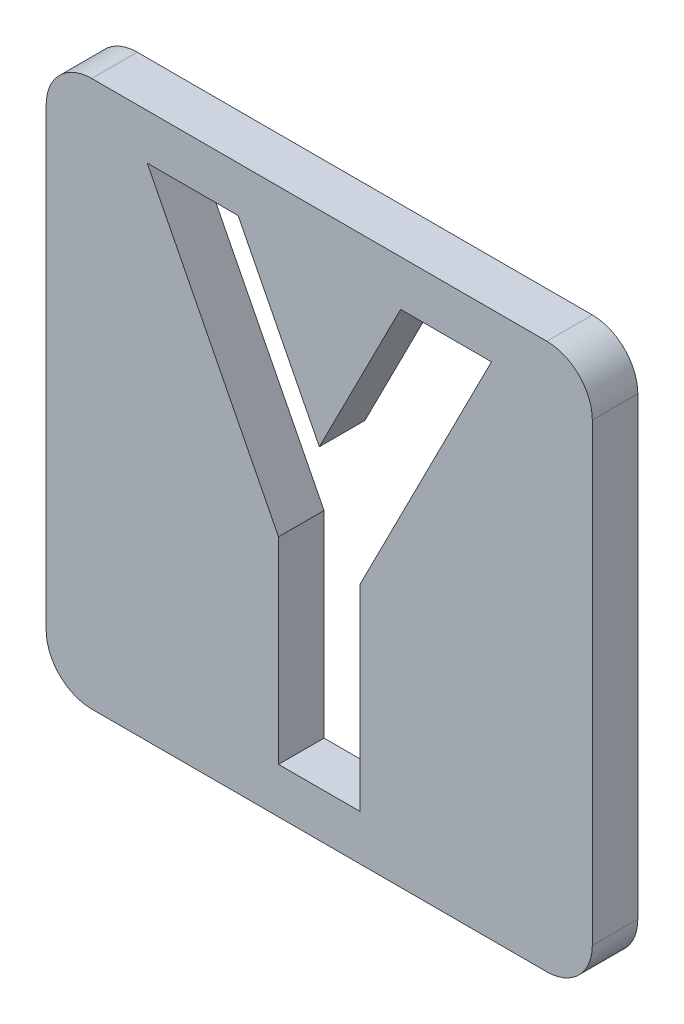
SolidWorks part; units mm, degrees
ref_plane "Front Plane" through (0, 0, 0) normal (0, 0, 1) x (1, 0, 0)
ref_plane "Top Plane" through (0, 0, 0) normal (0, 1, 0) x (1, 0, 0)
ref_plane "Right Plane" through (0, 0, 0) normal (1, 0, 0) x (0, 0, -1)
sketch "Sketch1" plane through (0, 0, 0) normal (0, 0, 1) x (1, 0, 0)
  line L1 (-50, 60) -> (50, 60)
  line L2 (-60, 50) -> (-60, -50)
  line L3 (-50, -60) -> (50, -60)
  line L4 (60, 50) -> (60, -50)
  line L5 (-60, 60) -> (60, -60) construction
  line L6 (-60, -60) -> (60, 60) construction
  arc A0 (-60, -50) -> (-50, -60) centre (-50, -50) ccw
  arc A1 (50, -60) -> (60, -50) centre (50, -50) ccw
  arc A2 (50, 60) -> (60, 50) centre (50, 50) cw
  arc A3 (-50, 60) -> (-60, 50) centre (-50, 50) ccw
  point P0 (0, 0)
  dimension "D3" = 10
  dimension "D1" = 120
  dimension "D2" = 120
extrude "Boss-Extrude1" add sketch "Sketch1" along normal blind 10 contours A3 L2 A0 L3 A1 L4 A2 L1
sketch "Sketch2" plane through (0, 0, 10) normal (0, 0, 1) x (1, 0, 0)
  line L0 (0, 0) -> (0, 40) construction
  line L1 (-50, 50) -> (50, 50) construction
  line L2 (-50, 50) -> (-50, -50) construction
  line L3 (-50, -50) -> (50, -50) construction
  line L4 (50, 50) -> (50, -50) construction
  line L5 (-50, 50) -> (50, -50) construction
  line L6 (-50, -50) -> (50, 50) construction
  line L7 (0, 40) -> (-40, 40) construction
  line L8 (-40, 40) -> (-40, 0) construction
  line L9 (-40, 0) -> (0, 0) construction
  line L11 (0, 20) -> (-20, 20) construction
  line L12 (-20, 40) -> (-20, 20) construction
  circle A0 centre (0, 40) radius 4 construction
  circle A1 centre (0, 20) radius 4 construction
  circle A2 centre (0, 0) radius 4 construction
  circle A3 centre (-20, 20) radius 4 construction
  circle A4 centre (-20, 40) radius 4 construction
  circle A5 centre (-40, 40) radius 4 construction
  circle A6 centre (0, 0) radius 4 construction
  circle A7 centre (20, 0) radius 4 construction
  circle A8 centre (40, 0) radius 4 construction
  circle A9 centre (40, 20) radius 4 construction
  circle A10 centre (40, 40) radius 4 construction
  circle A11 centre (20, 20) radius 4 construction
  circle A12 centre (0, 0) radius 4 construction
  circle A13 centre (0, -20) radius 4 construction
  circle A14 centre (0, -40) radius 4 construction
  circle A15 centre (20, -40) radius 4 construction
  circle A16 centre (40, -40) radius 4 construction
  circle A17 centre (20, -20) radius 4 construction
  circle A18 centre (0, 0) radius 4 construction
  circle A19 centre (-20, 0) radius 4 construction
  circle A20 centre (-40, 0) radius 4 construction
  circle A21 centre (-40, -20) radius 4 construction
  circle A22 centre (-40, -40) radius 4 construction
  circle A23 centre (-20, -20) radius 4 construction
  text T0 "Y" font "Century Gothic" height 100
  point P0 (0, 0)
  point P55 (0, 0)
  dimension "D4" = 8
  dimension "D1" = 100
  dimension "D2" = 100
  dimension "D3" = 40
  dimension "D5" = 4
extrude "Cut-Extrude38" cut sketch "Sketch2" against normal blind 10
